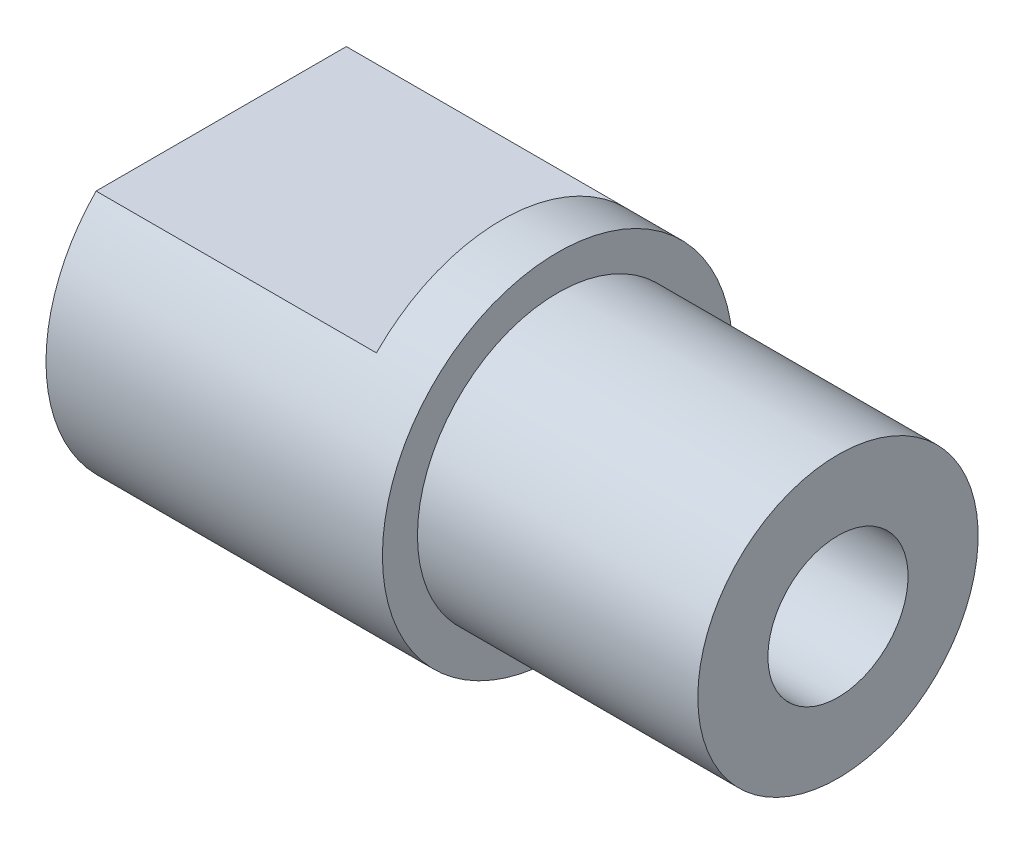
SolidWorks part; units mm, degrees
ref_plane "Front Plane" through (0, 0, 0) normal (0, 0, 1) x (1, 0, 0)
ref_plane "Top Plane" through (0, 0, 0) normal (0, 1, 0) x (1, 0, 0)
ref_plane "Right Plane" through (0, 0, 0) normal (1, 0, 0) x (0, 0, -1)
sketch "Sketch1" plane through (0, 0, 0) normal (0, 0, 1) x (1, 0, 0)
  line L0 (0, 0) -> (27.94, 0) construction
  line L1 (0, 3.175) -> (0, 7.9375)
  line L2 (0, 7.9375) -> (15.24, 7.9375)
  line L3 (15.24, 7.9375) -> (15.24, 6.35)
  line L4 (15.24, 6.35) -> (27.94, 6.35)
  line L5 (27.94, 6.35) -> (27.94, 3.175)
  line L6 (0, 0) -> (27.94, 0) construction
  line L7 (0, 3.175) -> (27.94, 3.175)
  point P9 (28.8538, 3.175)
  dimension "D1" = 15.875
  dimension "D2" = 12.7
  dimension "D3" = 15.24
  dimension "D4" = 12.7
  dimension "D5" = 6.35
revolve "Revolve1" add sketch "Sketch1" angle 360 about L0
sketch "Sketch2" plane through (0, 0, 0) normal (-1, 0, 0) x (0, 0, 1)
  line L0 (-5.6685, 5.5563) -> (5.6685, 5.5563)
  line L1 (-5.6685, -5.5562) -> (5.6685, -5.5562)
  circle A0 centre (0, 0) radius 7.9375 construction
  circle A1 centre (0, 0) radius 7.9375
  arc A2 (-5.6685, -5.5562) -> (5.6685, -5.5562) centre (0, 0) ccw
  arc A3 (5.6685, 5.5563) -> (-5.6685, 5.5563) centre (0, 0) ccw
  dimension "D2" = 11.1125
  dimension "D1" = 0
extrude "Cut-Extrude2" cut sketch "Sketch2" against normal blind 12.7
